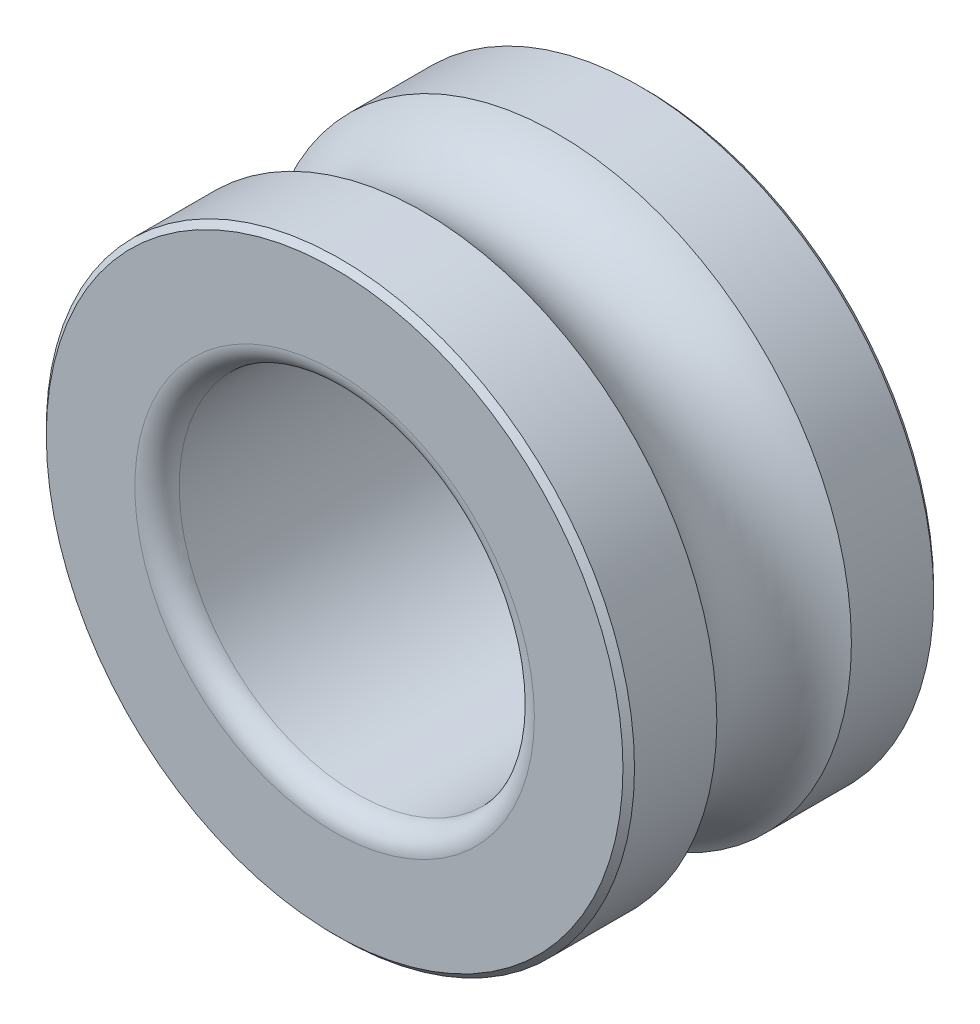
SolidWorks part; units mm, degrees
ref_plane "Front Plane" through (0, 0, 0) normal (0, 0, 1) x (1, 0, 0)
ref_plane "Top Plane" through (0, 0, 0) normal (0, 1, 0) x (1, 0, 0)
ref_plane "Right Plane" through (0, 0, 0) normal (1, 0, 0) x (0, 0, -1)
sketch "Sketch2" plane through (0, 0, 0) normal (1, 0, 0) x (0, 0, -1)
  line L0 (-3.5, 0) -> (3.5, 0) construction
  line L2 (3, 4) -> (-3, 4)
  line L3 (3.5, 4.5) -> (3.5, 6.495)
  line L5 (-3.5, 4.5) -> (-3.5, 6.495)
  line L6 (-3.37, 6.625) -> (-1.5155, 6.625)
  line L8 (1.5155, 6.625) -> (3.37, 6.625)
  line L12 (-3.5, 6.495) -> (-3.37, 6.625)
  line L13 (3.5, 6.495) -> (3.37, 6.625)
  arc A1 (-1.5155, 6.625) -> (1.5155, 6.625) centre (0, 7.5) ccw
  arc A4 (-3, 4) -> (-3.5, 4.5) centre (-3, 4.5) cw
  arc A5 (3.5, 4.5) -> (3, 4) centre (3, 4.5) cw
  point P3 (1.6479, 7.3167)
  point P9 (3.5, 6.625)
  point P10 (-0.0215, 7.0432)
  point P12 (0.0508, 7.0432)
  point P15 (-3.5, 6.625)
  dimension "D6" = 0
  dimension "D7" = 0.5
  dimension "D8" = 1.75
  dimension "D2" = 7.5
  dimension "D3" = 3.5
  dimension "D4" = 2.625
  dimension "D5" = 7
  dimension "D9" = 1.8545
  dimension "D10" = 0.13
  dimension "D11" = 0.13
  dimension "D12" = 0.13
  dimension "D13" = 0.13
revolve "Revolve1" add sketch "Sketch2" angle 360 about L0
